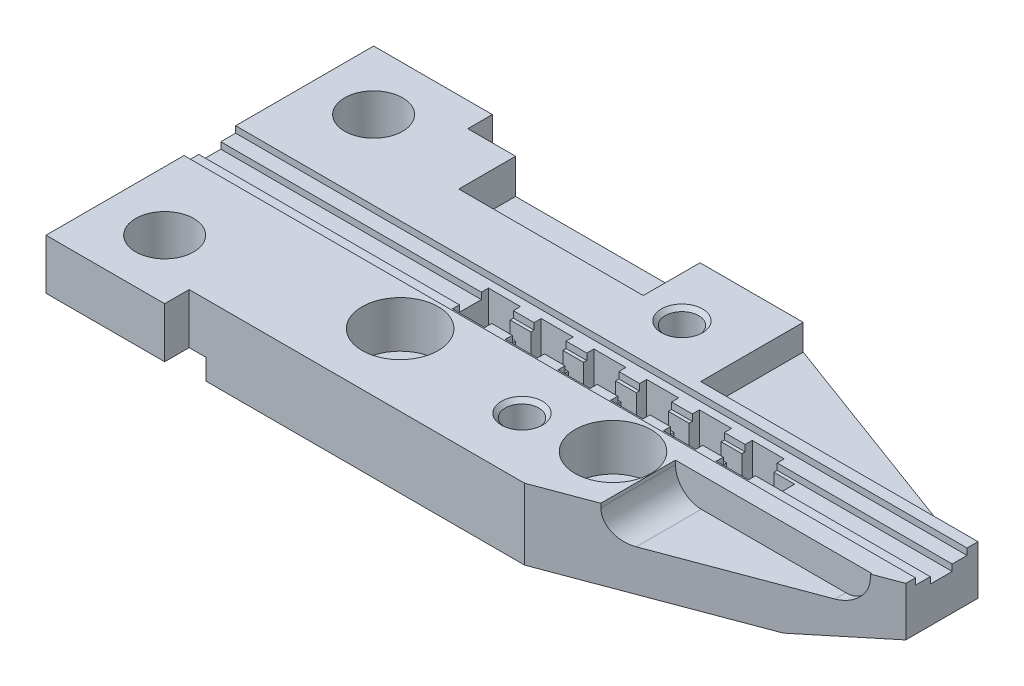
SolidWorks part; units mm, degrees
material "Gray Cast Iron"
ref_plane "Front Plane" through (0, 0, 0) normal (0, 0, 1) x (1, 0, 0)
ref_plane "Top Plane" through (0, 0, 0) normal (0, 1, 0) x (1, 0, 0)
ref_plane "Right Plane" through (0, 0, 0) normal (1, 0, 0) x (0, 0, -1)
sketch "Sketch1" plane through (0, 0, 0) normal (0, 0, 1) x (1, 0, 0)
  line L1 (-65.0008, -10.6723) -> (7.0082, -10.6723)
  line L2 (-65.0008, -10.6723) -> (-65.0008, -17.6573)
  line L3 (-65.0008, -17.6573) -> (7.0082, -17.6573)
  line L4 (7.0082, -10.6723) -> (7.0082, -17.6573)
  dimension "D1" = 6.985
  dimension "D2" = 72.009
extrude "Boss-Extrude1" add sketch "Sketch1" against normal blind 32.258
sketch "Sketch2" plane through (0, 0, 0) normal (0, 0, 1) x (1, 0, 0)
  line L1 (-65.0008, -17.6573) -> (-51.6658, -17.6573)
  line L2 (-65.0008, -17.6573) -> (-65.0008, -15.6253)
  line L3 (-65.0008, -15.6253) -> (-51.6658, -15.6253)
  line L4 (-51.6658, -17.6573) -> (-51.6658, -15.6253)
  dimension "D1" = 2.032
  dimension "D2" = 13.335
extrude "Cut-Extrude1" cut sketch "Sketch2" against normal through all
sketch "Sketch3" plane through (0, 0, 0) normal (0, 0, 1) x (1, 0, 0)
  line L0 (7.0082, -10.6723) -> (-14.8358, -10.6723) construction
  line L1 (7.0082, -10.6723) -> (-65.0008, -10.6723) construction
  line L3 (-14.8358, -10.6723) -> (4.4682, -10.6723)
  line L4 (-14.8358, -10.6723) -> (-14.8358, -13.5933)
  line L5 (-14.8358, -13.5933) -> (4.4682, -13.5933)
  line L6 (4.4682, -10.6723) -> (4.4682, -13.5933)
  dimension "D1" = 21.844
  dimension "D2" = 19.304
  dimension "D3" = 2.921
extrude "Cut-Extrude2" cut sketch "Sketch3" against normal blind 11.811
fillet "Fillet1" radius 2.54 2 edges at (4.4682, -13.5933, -5.9055) (-14.8358, -13.5933, -5.9055)
sketch "Sketch4" plane through (0, 0, 0) normal (0, 0, 1) x (1, 0, 0)
  line L0 (7.0082, -10.6723) -> (7.0082, -15.4983) construction
  line L1 (7.0082, -17.6573) -> (7.0082, -10.6723) construction
  line L2 (-51.6658, -17.6573) -> (-1.7548, -17.6573)
  line L3 (-51.6658, -17.6573) -> (7.0082, -17.6573) construction
  line L4 (7.0082, -15.4983) -> (-1.7548, -17.6573)
  line L5 (7.0082, -17.6573) -> (7.0082, -15.4983)
  line L6 (7.0082, -17.6573) -> (-1.7548, -17.6573)
  line M6 (-51.6658, -17.6573) -> (7.0082, -17.6573)
  line M7 (7.0082, -17.6573) -> (7.0082, -10.6723)
  dimension "D1" = 4.826
  dimension "D2" = 49.911
extrude "Cut-Extrude3" cut sketch "Sketch4" against normal through all contours L4 M7 M6
sketch "Sketch5" plane through (0, -10.6723, 0) normal (0, 1, 0) x (1, 0, 0)
  line L0 (7.0082, 16.129) -> (-65.0008, 16.129) construction
  line L1 (7.0082, 32.258) -> (7.0082, 0) construction
  line L2 (-65.0008, 32.258) -> (-65.0008, 0) construction
  line L3 (-65.0008, 19.6215) -> (7.0082, 19.6215) construction
  line L4 (-65.0008, 12.6365) -> (7.0082, 12.6365) construction
  dimension "D1" = 6.985
  dimension "D2" = 3.4925
sketch "Sketch6" plane through (0, -10.6723, 0) normal (0, 1, 0) x (1, 0, 0)
  line L2 (7.0082, 32.258) -> (-65.0008, 32.258) construction
  line L5 (-53.3168, 32.258) -> (7.0082, 32.258)
  line L6 (-53.3168, 32.258) -> (-53.3168, 29.845)
  line L7 (-53.3168, 29.845) -> (7.0082, 29.845)
  line L8 (7.0082, 32.258) -> (7.0082, 29.845)
  line L9 (7.0082, 32.258) -> (7.0082, 0) construction
  line L10 (-14.8358, 0) -> (-65.0008, 0) construction
  line L11 (-53.3168, 0) -> (7.0082, 0)
  line L12 (-53.3168, 0) -> (-53.3168, 2.413)
  line L13 (-53.3168, 2.413) -> (7.0082, 2.413)
  line L14 (7.0082, 0) -> (7.0082, 2.413)
  line L15 (-65.0008, 32.258) -> (-65.0008, 0) construction
  dimension "D1" = 11.684
  dimension "D2" = 11.684
  dimension "D3" = 2.413
  dimension "D4" = 2.413
extrude "Cut-Extrude6" cut sketch "Sketch6" against normal through all
sketch "Sketch11" plane through (0, -10.6723, 0) normal (0, 1, 0) x (1, 0, 0)
  line L0 (-65.0008, 29.845) -> (-48.6178, 29.845) construction
  line L1 (-65.0008, 32.258) -> (-65.0008, 0) construction
  line L2 (-53.3168, 29.845) -> (7.0082, 29.845) construction
  line L4 (-48.6178, 29.845) -> (-30.4568, 29.845)
  line L5 (-48.6178, 29.845) -> (-48.6178, 24.257)
  line L6 (-48.6178, 24.257) -> (-30.4568, 24.257)
  line L7 (-30.4568, 29.845) -> (-30.4568, 24.257)
  dimension "D1" = 16.383
  dimension "D2" = 5.588
  dimension "D3" = 18.161
extrude "Cut-Extrude7" cut sketch "Sketch11" against normal blind 3.429
sketch "Sketch12" plane through (0, -14.1013, 0) normal (0, 1, 0) x (1, 0, 0)
  line L0 (-30.4568, 24.257) -> (-30.4568, 29.845) construction
  line L1 (-48.6178, 24.257) -> (-30.4568, 24.257)
  line L2 (-48.6178, 24.257) -> (-48.6178, 27.432)
  line L3 (-48.6178, 27.432) -> (-30.4568, 27.432)
  line L4 (-30.4568, 24.257) -> (-30.4568, 27.432)
  dimension "D1" = 3.175
extrude "Cut-Extrude8" cut sketch "Sketch12" against normal through all
sketch "Sketch13" plane through (0, 0, -29.845) normal (0, 0, -1) x (-1, 0, 0)
  line L0 (30.4568, -10.6723) -> (20.2968, -10.6723) construction
  line L1 (65.0008, -10.6723) -> (-7.0082, -10.6723) construction
  line L3 (20.2968, -10.6723) -> (-10.0173, -10.6723)
  line L4 (20.2968, -10.6723) -> (20.2968, -13.2123)
  line L5 (20.2968, -13.2123) -> (-10.0173, -13.2123)
  line L6 (-10.0173, -10.6723) -> (-10.0173, -13.2123)
  dimension "D1" = 10.16
  dimension "D2" = 2.54
extrude "Cut-Extrude9" cut sketch "Sketch13" against normal blind 10.0965
sketch "Sketch14" plane through (0, -10.6723, 0) normal (0, 1, 0) x (1, 0, 0)
  line L0 (-20.2968, 29.845) -> (-20.2968, 2.413) construction
  line L1 (-14.8358, 2.413) -> (-53.3168, 2.413) construction
  line L2 (-20.2968, 29.845) -> (7.0082, 19.7485)
  line L3 (7.0082, 19.7485) -> (7.0082, 29.845)
  line L4 (7.0082, 19.7485) -> (7.0082, 29.845) construction
  line L5 (7.0082, 29.845) -> (-20.2968, 29.845)
  line L6 (-20.2968, 2.413) -> (7.0082, 12.6365)
  line L7 (7.0082, 12.6365) -> (7.0082, 2.413)
  line L8 (7.0082, 2.413) -> (-20.2968, 2.413)
extrude "Cut-Extrude10" cut sketch "Sketch14" against normal through all
fillet "Fillet2" radius 0.635 1 edges at (-6.6443, -13.2123, -19.7485)
sketch "Sketch16" plane through (-65.0008, 0, 0) normal (-1, 0, 0) x (0, 0, 1)
  line L0 (-16.129, -10.6723) -> (-16.129, -11.9423) construction
  line L1 (-32.258, -10.6723) -> (0, -10.6723) construction
  line L2 (-32.258, -15.6253) -> (0, -15.6253) construction
  line L3 (-17.2085, -11.9423) -> (-15.0495, -11.9423)
  line L4 (-18.669, -10.6723) -> (-13.589, -10.6723)
  line L5 (-18.669, -10.6723) -> (-18.669, -11.3073)
  line L6 (-13.589, -10.6723) -> (-13.589, -11.3073)
  line L7 (-18.669, -11.3073) -> (-17.2085, -11.3073)
  line L8 (-17.2085, -11.3073) -> (-17.2085, -11.9423)
  line L9 (-13.589, -11.3073) -> (-15.0495, -11.3073)
  line L10 (-15.0495, -11.3073) -> (-15.0495, -11.9423)
  point P4 (-16.129, -15.6253)
  dimension "D1" = 3.683
  dimension "D2" = 2.159
  dimension "D3" = 1.0795
  dimension "D4" = 5.08
  dimension "D5" = 2.54
  dimension "D6" = 0.635
  dimension "D7" = 0.635
extrude "Cut-Extrude11" cut sketch "Sketch16" against normal through all
sketch "Sketch17" plane through (0, -17.6573, 0) normal (0, -1, 0) x (1, 0, 0)
  line L0 (-51.6658, -16.129) -> (-39.3468, -16.129) construction
  line L1 (-51.6658, -29.845) -> (-51.6658, -2.413) construction
  line L2 (7.0082, -16.129) -> (-65.0008, -16.129) construction
  line L3 (-39.3468, -17.907) -> (-39.3468, -14.351)
  line L4 (-39.3468, -14.351) -> (-36.1718, -14.351)
  line L5 (-39.3468, -17.907) -> (-36.1972, -17.907)
  line L6 (-36.1972, -17.907) -> (-36.1972, -16.891)
  line L7 (-36.1972, -16.891) -> (-34.1652, -16.891)
  line L8 (-36.1718, -14.351) -> (-36.1718, -15.367)
  line L9 (-36.1718, -15.367) -> (-34.1398, -15.367)
  line L10 (-34.1525, -14.351) -> (-30.9775, -14.351)
  line L11 (-30.9775, -15.367) -> (-28.9455, -15.367)
  line L12 (-31.0029, -16.891) -> (-28.9709, -16.891)
  line L13 (-30.9775, -14.351) -> (-30.9775, -15.367)
  line L14 (-31.0029, -17.907) -> (-31.0029, -16.891)
  line L15 (-34.1525, -17.907) -> (-31.0029, -17.907)
  line L16 (-8.1683, -15.367) -> (-8.1937, -16.891)
  line L17 (-28.9582, -14.351) -> (-25.7832, -14.351)
  line L18 (-25.7832, -15.367) -> (-23.7512, -15.367)
  line L19 (-25.8086, -16.891) -> (-23.7766, -16.891)
  line L20 (-25.7832, -14.351) -> (-25.7832, -15.367)
  line L21 (-25.8086, -17.907) -> (-25.8086, -16.891)
  line L22 (-28.9582, -17.907) -> (-25.8086, -17.907)
  line L23 (-13.3753, -14.351) -> (-13.3626, -15.367)
  line L24 (-23.7639, -14.351) -> (-20.5889, -14.351)
  line L25 (-20.5889, -15.367) -> (-18.5569, -15.367)
  line L26 (-20.6143, -16.891) -> (-18.5823, -16.891)
  line L27 (-20.5889, -14.351) -> (-20.5889, -15.367)
  line L28 (-20.6143, -17.907) -> (-20.6143, -16.891)
  line L29 (-23.7639, -17.907) -> (-20.6143, -17.907)
  line L30 (-13.3753, -17.907) -> (-13.388, -16.891)
  line L31 (-18.5696, -14.351) -> (-15.3946, -14.351)
  line L32 (-15.3946, -15.367) -> (-13.3626, -15.367)
  line L33 (-15.42, -16.891) -> (-13.388, -16.891)
  line L34 (-15.3946, -14.351) -> (-15.3946, -15.367)
  line L35 (-15.42, -17.907) -> (-15.42, -16.891)
  line L36 (-18.5696, -17.907) -> (-15.42, -17.907)
  line L37 (-18.5696, -14.351) -> (-18.5569, -15.367)
  line L38 (-13.3753, -14.351) -> (-10.2003, -14.351)
  line L39 (-10.2003, -15.367) -> (-8.1683, -15.367)
  line L40 (-10.2257, -16.891) -> (-8.1937, -16.891)
  line L41 (-10.2003, -14.351) -> (-10.2003, -15.367)
  line L42 (-10.2257, -17.907) -> (-10.2257, -16.891)
  line L43 (-13.3753, -17.907) -> (-10.2257, -17.907)
  line L44 (-18.5823, -16.891) -> (-18.5696, -17.907)
  line L45 (-39.3468, -14.351) -> (-34.1525, -14.351) construction
  line L46 (-34.1525, -17.907) -> (-34.1525, -14.351) [skipped]
  line L47 (-28.9582, -17.907) -> (-28.9582, -14.351) [skipped]
  line L48 (-23.7639, -17.907) -> (-23.7639, -14.351) [skipped]
  line L49 (-18.5696, -17.907) -> (-18.5696, -14.351) [skipped]
  line L50 (-13.3753, -17.907) -> (-13.3753, -14.351) [skipped]
  line L51 (-23.7639, -14.351) -> (-23.7512, -15.367)
  line L52 (-23.7766, -16.891) -> (-23.7639, -17.907)
  line L53 (-34.1525, -14.351) -> (-34.1398, -15.367)
  line L54 (-34.1652, -16.891) -> (-34.1525, -17.907)
  line L55 (-34.1525, -17.907) -> (-34.0988, -17.9489)
  line L56 (-28.9455, -15.367) -> (-28.9582, -14.351)
  line L57 (-28.9709, -16.891) -> (-28.9582, -17.907)
  dimension "D1" = 12.319
  dimension "D2" = 3.556
  dimension "D3" = 1.778
  dimension "D4" = 3.175
  dimension "D5" = 3.1496
  dimension "D6" = 1.524
  dimension "D7" = 1.016
  dimension "D8" = 2.032
  dimension "D9" = 2.032
  dimension "D11" = 5.1943
  dimension "D10" = 6
extrude "Cut-Extrude12" cut sketch "Sketch17" against normal through all contours L12 L57 L22 L21 L19 L52 L29 L28 L26 L44 L36 L35 L33 L30 L43 L42 L40 L16 L39 L41 L38 L23 L32 L34 L31 L37 L25 L27 L24 L51 L18 L20 L17 L56 L11 L13 L10 L53 L9 L8 L4 L3 L5 L6 L7 L54 L15 L14
sketch "Sketch18" plane through (0, -17.6573, 0) normal (0, -1, 0) x (1, 0, 0)
  circle A0 centre (-8.8296, -13.1407) radius 0.7586
  circle A1 centre (-40.8784, -14.7887) radius 0.8674
  dimension "D1" = 1.7347
  dimension "D2" = 1.5173
extrude "Cut-Extrude13" cut sketch "Sketch18" against normal blind 2.4765
sketch "Sketch19" plane through (0, -15.6253, 0) normal (0, -1, 0) x (1, 0, 0)
  line L0 (-59.1588, 0) -> (-59.1588, -5.842) construction
  line L1 (-53.3168, 0) -> (-65.0008, 0) construction
  line L2 (-59.1588, -5.842) -> (-65.0008, -5.842) construction
  line L3 (-65.0008, -32.258) -> (-65.0008, 0) construction
  line L4 (-59.1588, -32.258) -> (-59.1588, -26.416) construction
  line L5 (-53.3168, -32.258) -> (-65.0008, -32.258) construction
  line L6 (-59.1588, -26.416) -> (-65.0008, -26.416) construction
  circle A0 centre (-59.1588, -5.842) radius 2.8575
  circle A1 centre (-59.1588, -26.416) radius 2.8575
  dimension "D4" = 5.715
  dimension "D5" = 5.715
  dimension "D1" = 5.842
  dimension "D2" = 5.842
  dimension "D3" = 5.842
extrude "Cut-Extrude14" cut sketch "Sketch19" against normal through all
chamfer "Chamfer1" distance 0.381 angle 45 2 edges at (-59.1588, -15.6253, -8.6995) (-59.1588, -15.6253, -29.2735)
sketch "Sketch20" plane through (0, -17.6573, 0) normal (0, -1, 0) x (1, 0, 0)
  line L0 (-51.6658, -8.255) -> (-26.3928, -8.255) construction
  line L1 (-51.6658, -29.845) -> (-51.6658, -2.413) construction
  line L2 (-26.3928, -8.255) -> (-26.3928, -2.413) construction
  line L3 (-20.2968, -2.413) -> (-51.6658, -2.413) construction
  line L4 (-51.6658, -24.003) -> (-26.3928, -24.003) construction
  line L5 (-26.3928, -24.003) -> (-26.3928, -29.845) construction
  line L6 (-51.6658, -29.845) -> (-20.2968, -29.845) construction
  circle A0 centre (-26.3928, -8.255) radius 1.651
  circle A1 centre (-26.3928, -24.003) radius 1.651
  dimension "D5" = 3.302
  dimension "D6" = 3.302
  dimension "D1" = 25.273
  dimension "D2" = 25.273
  dimension "D3" = 5.842
  dimension "D4" = 5.842
extrude "Cut-Extrude15" cut sketch "Sketch20" against normal through all
chamfer "Chamfer2" distance 0.381 angle 45 4 edges at (-24.7418, -17.6573, -24.003) (-24.7418, -17.6573, -8.255) (-24.7418, -10.6723, -8.255) (-24.7418, -10.6723, -24.003)
sketch "Sketch21" plane through (0, -17.6573, 0) normal (0, -1, 0) x (1, 0, 0)
  line L0 (-39.6008, -9.4684) -> (-18.6458, -9.4684) construction
  line L1 (-36.1718, -15.367) -> (-34.1398, -15.367) construction
  line L2 (-51.6658, -29.845) -> (-51.6658, -2.413) construction
  circle A0 centre (-39.6008, -9.4684) radius 2.159
  circle A1 centre (-18.6458, -9.4684) radius 2.159
  dimension "D2" = 4.318
  dimension "D3" = 4.318
  dimension "D5" = 12.065
  dimension "D1" = 20.955
  dimension "D4" = 5.8986
extrude "Cut-Extrude16" cut sketch "Sketch21" against normal through all
sketch "Sketch22" plane through (0, -10.6723, 0) normal (0, 1, 0) x (1, 0, 0)
  circle A0 centre (-39.6008, 9.4684) radius 3.7465
  circle A1 centre (-18.6458, 9.4684) radius 3.7465
  dimension "D1" = 7.493
  dimension "D2" = 7.493
extrude "Cut-Extrude17" cut sketch "Sketch22" against normal blind 4.572
